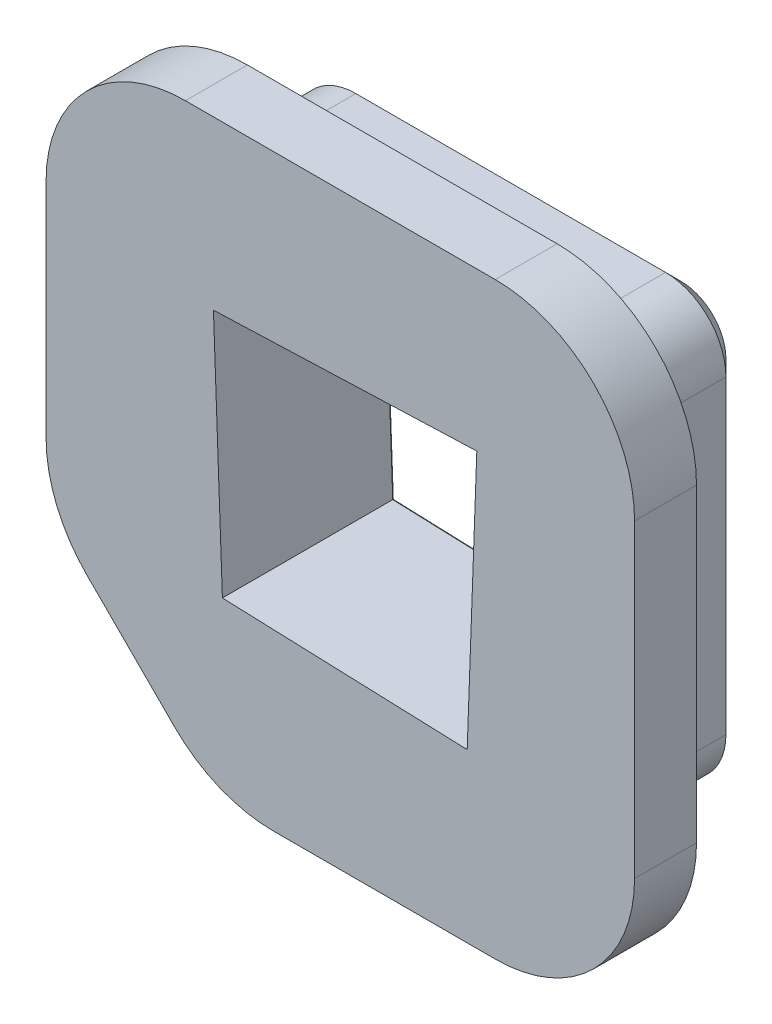
SolidWorks part; units mm, degrees
ref_plane "Front Plane" through (0, 0, 0) normal (0, 0, 1) x (1, 0, 0)
ref_plane "Top Plane" through (0, 0, 0) normal (0, 1, 0) x (1, 0, 0)
ref_plane "Right Plane" through (0, 0, 0) normal (1, 0, 0) x (0, 0, -1)
sketch "Sketch1" plane through (0, 0, 0) normal (0, 0, 1) x (1, 0, 0)
  line L51 (-12.8997, -10.9497) -> (-22.8997, -10.9497)
  line L52 (-10.9497, -22.8997) -> (-10.9497, -12.8997)
  line L53 (-20.0712, -24.8497) -> (-12.8997, -24.8497)
  line L54 (-24.2785, -21.4501) -> (-21.4501, -24.2785)
  line L55 (-24.8497, -12.8997) -> (-24.8497, -20.0712)
  line L56 (-12.8997, -10.9497) -> (-22.8997, -10.9497)
  line L57 (-10.9497, -22.8997) -> (-10.9497, -12.8997)
  line L58 (-20.0712, -24.8497) -> (-12.8997, -24.8497)
  line L59 (-24.2785, -21.4501) -> (-21.4501, -24.2785)
  line L60 (-24.8497, -12.8997) -> (-24.8497, -20.0712)
  arc A52 (-10.9497, -12.8997) -> (-12.8997, -10.9497) centre (-12.8997, -12.8997) ccw
  arc A53 (-12.8997, -24.8497) -> (-10.9497, -22.8997) centre (-12.8997, -22.8997) ccw
  arc A54 (-21.4501, -24.2785) -> (-20.0712, -24.8497) centre (-20.0712, -22.8997) ccw
  arc A55 (-24.8497, -20.0712) -> (-24.2785, -21.4501) centre (-22.8997, -20.0712) ccw
  arc A56 (-22.8997, -10.9497) -> (-24.8497, -12.8997) centre (-22.8997, -12.8997) ccw
  arc A57 (-10.9497, -12.8997) -> (-12.8997, -10.9497) centre (-12.8997, -12.8997) ccw
  arc A58 (-12.8997, -24.8497) -> (-10.9497, -22.8997) centre (-12.8997, -22.8997) ccw
  arc A59 (-21.4501, -24.2785) -> (-20.0712, -24.8497) centre (-20.0712, -22.8997) ccw
  arc A60 (-24.8497, -20.0712) -> (-24.2785, -21.4501) centre (-22.8997, -20.0712) ccw
  arc A61 (-22.8997, -10.9497) -> (-24.8497, -12.8997) centre (-22.8997, -12.8997) ccw
  dimension "D1" = 0.05
sketch "Sketch2" plane through (0, 0, 0) normal (0, 0, 1) x (1, 0, 0)
  line L67 (-26.0816, -23.2532) -> (-23.2532, -26.0816)
  line L68 (-20.0712, -27.3997) -> (-12.8997, -27.3997)
  line L69 (-8.3997, -22.8997) -> (-8.3997, -12.8997)
  line L70 (-12.8997, -8.3997) -> (-22.8997, -8.3997)
  line L71 (-27.3997, -12.8997) -> (-27.3997, -20.0712)
  line L72 (-26.0816, -23.2532) -> (-23.2532, -26.0816)
  line L73 (-20.0712, -27.3997) -> (-12.8997, -27.3997)
  line L74 (-8.3997, -22.8997) -> (-8.3997, -12.8997)
  line L75 (-12.8997, -8.3997) -> (-22.8997, -8.3997)
  line L76 (-27.3997, -12.8997) -> (-27.3997, -20.0712)
  arc A66 (-27.3997, -20.0712) -> (-26.0816, -23.2532) centre (-22.8997, -20.0712) ccw
  arc A67 (-23.2532, -26.0816) -> (-20.0712, -27.3997) centre (-20.0712, -22.8997) ccw
  arc A68 (-12.8997, -27.3997) -> (-8.3997, -22.8997) centre (-12.8997, -22.8997) ccw
  arc A69 (-8.3997, -12.8997) -> (-12.8997, -8.3997) centre (-12.8997, -12.8997) ccw
  arc A70 (-22.8997, -8.3997) -> (-27.3997, -12.8997) centre (-22.8997, -12.8997) ccw
  arc A71 (-27.3997, -20.0712) -> (-26.0816, -23.2532) centre (-22.8997, -20.0712) ccw
  arc A72 (-23.2532, -26.0816) -> (-20.0712, -27.3997) centre (-20.0712, -22.8997) ccw
  arc A73 (-12.8997, -27.3997) -> (-8.3997, -22.8997) centre (-12.8997, -22.8997) ccw
  arc A74 (-8.3997, -12.8997) -> (-12.8997, -8.3997) centre (-12.8997, -12.8997) ccw
  arc A75 (-22.8997, -8.3997) -> (-27.3997, -12.8997) centre (-22.8997, -12.8997) ccw
  dimension "D1" = 2.5
sketch "Sketch3" plane through (0, 0, 0) normal (0, 0, 1) x (1, 0, 0)
  line L0 (-21.9956, -13.8037) -> (-13.493, -13.493)
  line L1 (-17.75, -130) -> (-22.5, 0) construction
  line L2 (-17.75, -130) -> (-13, 0) construction
  line L3 (-13.493, -13.493) -> (-13.8037, -21.9956)
  line L4 (0, -22.5) -> (-130, -17.75) construction
  line L5 (-13.8037, -21.9956) -> (-21.7069, -21.7069)
  line L6 (-21.7069, -21.7069) -> (-21.9956, -13.8037)
  line L7 (-130, -17.75) -> (0, -13) construction
extrude "Boss-Extrude1" add sketch "Sketch2" along normal blind 2
extrude "Boss-Extrude2" add sketch "Sketch1" against normal blind 4
extrude "Cut-Extrude1" cut sketch "Sketch3" along normal through all both and the other way through all
sketch "Sketch4" plane through (0, 0, 2) normal (0, 0, 1) x (1, 0, 0)
  line L0 (-26.0816, -23.2532) -> (-23.2532, -26.0816) construction
  line L1 (-16.6232, -20.2974) -> (-15.2783, -15.2783)
  line L2 (-15.2783, -15.2783) -> (-20.2974, -16.6232)
  line L3 (-20.2974, -16.6232) -> (-16.6232, -20.2974)
  line L4 (-12.8997, -8.3997) -> (-22.8997, -8.3997) construction
  line L5 (-8.3997, -22.8997) -> (-8.3997, -12.8997) construction
  circle A0 centre (-17.3997, -17.3997) radius 1.5 construction
  dimension "D1" = 3
  dimension "D2" = 9
  dimension "D3" = 9
extrude "Cut-Extrude2" [suppressed] cut sketch "Sketch4" against normal through all
chamfer "Chamfer1" distance 0.5 angle 45 14 edges at (-24.7012, -20.8175, -4) (-22.8643, -22.8643, -4) (-24.8497, -16.4854, -4) (-20.8175, -24.7012, -4) (-24.2785, -11.5208, -4) (-16.4854, -24.8497, -4) (-17.8997, -10.9497, -4) (-11.5208, -24.2785, -4) (-11.5208, -11.5208, -4) (-10.9497, -17.8997, -4) (-13.6484, -17.7443, -4) (-17.7443, -13.6484, -4) (-21.8512, -17.7553, -4) (-17.7553, -21.8512, -4)
